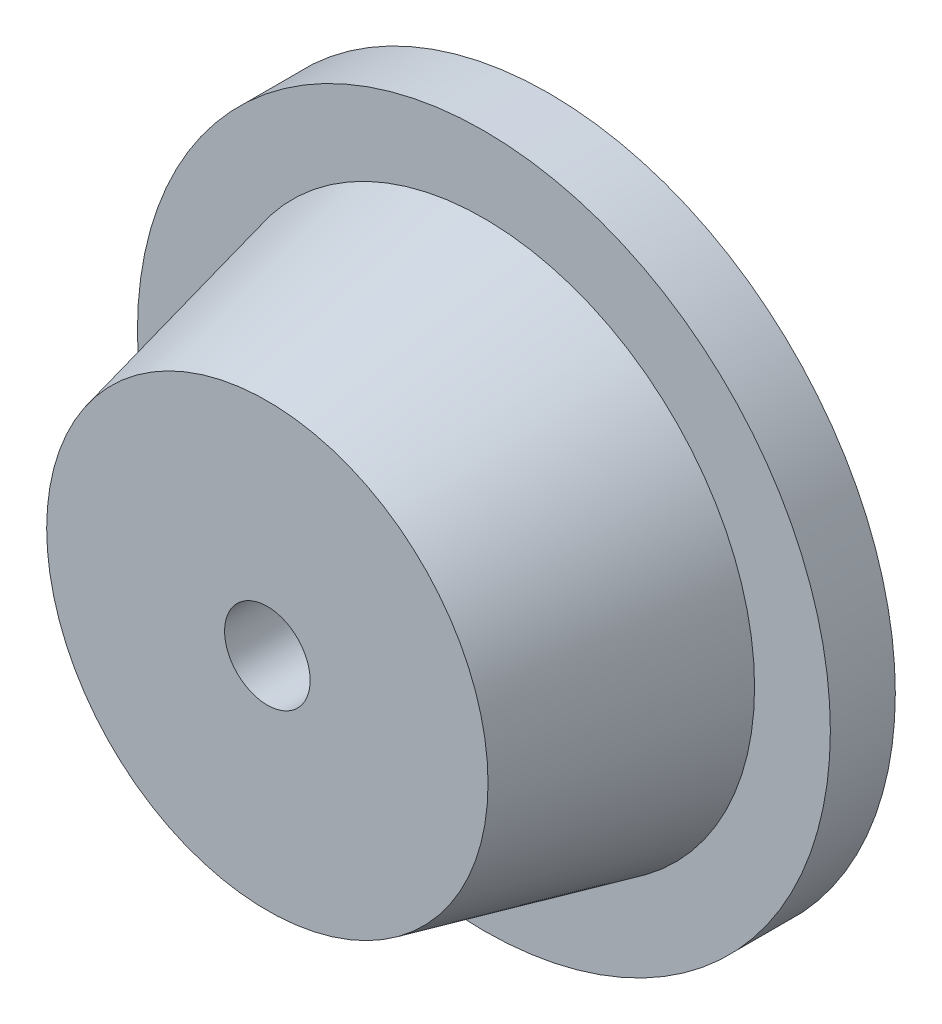
SolidWorks part; units mm, degrees
ref_plane "Front Plane" through (0, 0, 0) normal (0, 0, 1) x (1, 0, 0)
ref_plane "Top Plane" through (0, 0, 0) normal (0, 1, 0) x (1, 0, 0)
ref_plane "Right Plane" through (0, 0, 0) normal (1, 0, 0) x (0, 0, -1)
sketch "Sketch1" plane through (0, 0, 0) normal (0, 0, 1) x (1, 0, 0)
  circle A0 centre (0, 0) radius 16
  dimension "D1" = 32
extrude "Boss-Extrude1" add sketch "Sketch1" along normal blind 3
sketch "Sketch2" plane through (0, 0, 3) normal (0, 0, 1) x (1, 0, 0)
  circle A0 centre (0, 0) radius 12.5
  dimension "D1" = 25
extrude "Boss-Extrude2" add sketch "Sketch2" along normal blind 10 draft 13
sketch "Sketch3" plane through (0, 0, 13) normal (0, 0, 1) x (1, 0, 0)
  circle A0 centre (0, 0) radius 1.975
  dimension "D1" = 3.95
extrude "Cut-Extrude1" cut sketch "Sketch3" against normal through all
